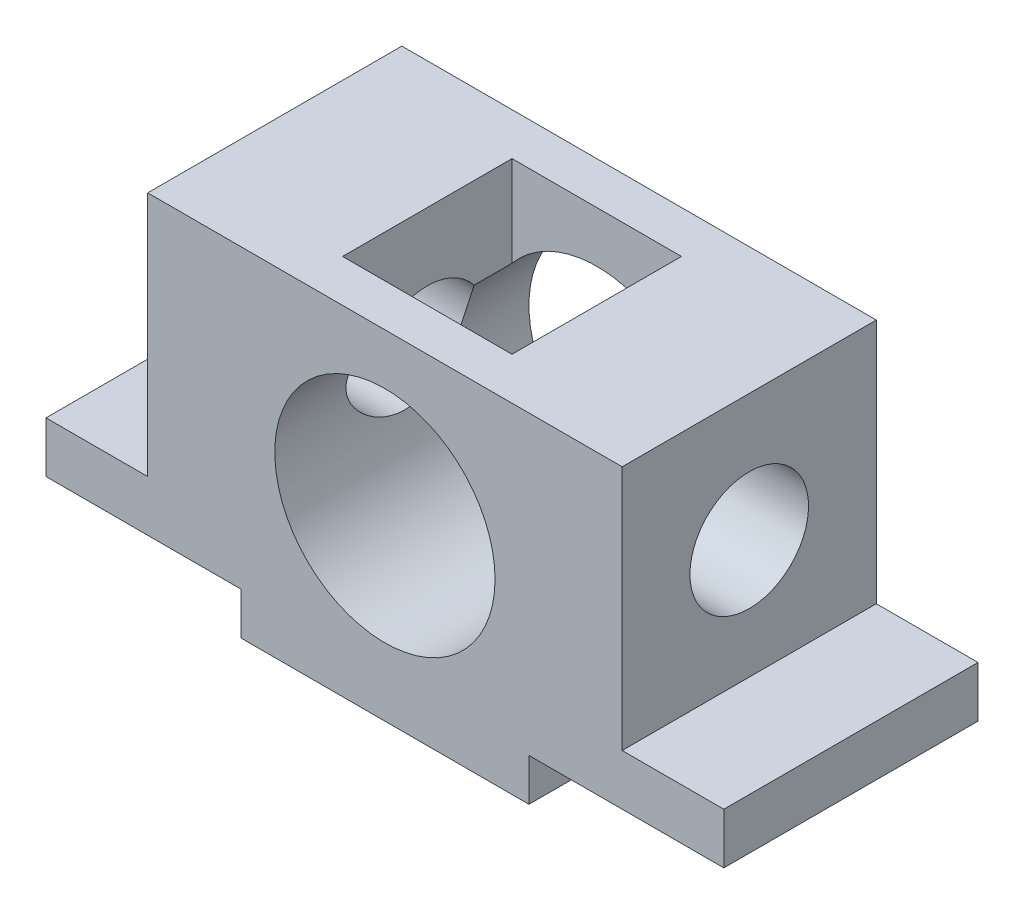
SolidWorks part; units mm, degrees
ref_plane "Спереди" through (0, 0, 0) normal (0, 0, 1) x (1, 0, 0)
ref_plane "Сверху" through (0, 0, 0) normal (0, 1, 0) x (1, 0, 0)
ref_plane "Справа" through (0, 0, 0) normal (1, 0, 0) x (0, 0, -1)
sketch "Эскиз1" plane through (0, 0, 0) normal (0, 0, 1) x (1, 0, 0)
  line L0 (-40, -15) -> (-17, -15)
  line L1 (28, -9) -> (28, 20)
  line L2 (-28, -9) -> (-28, 20)
  line L3 (-28, 20) -> (28, 20)
  line L7 (17, -15) -> (40, -15)
  line L8 (-17, -15) -> (-17, -20)
  line L9 (17, -15) -> (17, -20)
  line L10 (-17, -20) -> (17, -20)
  line L11 (-40, -9) -> (-28, -9)
  line L12 (40, -9) -> (28, -9)
  line L13 (-40, -9) -> (-40, -15)
  line L14 (40, -15) -> (40, -9)
  dimension "D2" = 40
  dimension "D3" = 23
  dimension "D4" = 29
  dimension "D5" = 23
  dimension "D6" = 56
  dimension "D7" = 34
  dimension "D8" = 12
  dimension "D9" = 12
  dimension "D10" = 6
extrude "Бобышка-Вытянуть1" add sketch "Эскиз1" along normal blind 30
sketch "Эскиз2" plane through (0, 0, 30) normal (0, 0, 1) x (1, 0, 0)
  line L0 (-17, -20) -> (17, -20) construction
  circle A0 centre (0, 1) radius 13
  dimension "D1" = 21
  dimension "D2" = 26
extrude "Вырез-Вытянуть1" cut sketch "Эскиз2" against normal through all
sketch "Эскиз3" plane through (-28, 0, 0) normal (-1, 0, 0) x (0, 0, 1)
  line L0 (30, 20) -> (0, 20) construction
  line L1 (30, 20) -> (30, -9) construction
  circle A0 centre (15, 5) radius 7
  point P4 (30, 5.5)
  dimension "D1" = 15
  dimension "D3" = 14
  dimension "D2" = 15
extrude "Вырез-Вытянуть2" cut sketch "Эскиз3" against normal through all
sketch "Эскиз4" plane through (0, 20, 0) normal (0, 1, 0) x (1, 0, 0)
  line L0 (-28, -30) -> (-28, 0) construction
  line L2 (28, -30) -> (28, 0) construction
  line L3 (-10, -5) -> (10, -5)
  line L4 (-10, -5) -> (-10, -25)
  line L5 (-10, -25) -> (10, -25)
  line L6 (10, -5) -> (10, -25)
  line L7 (-10, -5) -> (10, -25) construction
  line L8 (-10, -25) -> (10, -5) construction
  line L9 (28, -30) -> (-28, -30) construction
  line L10 (28, 0) -> (-28, 0) construction
  point P5 (0, -15)
  dimension "D1" = 20
  dimension "D2" = 20
  dimension "D3" = 18
  dimension "D4" = 18
  dimension "D5" = 5
  dimension "D6" = 5
extrude "Вырез-Вытянуть3" cut sketch "Эскиз4" against normal up to next
